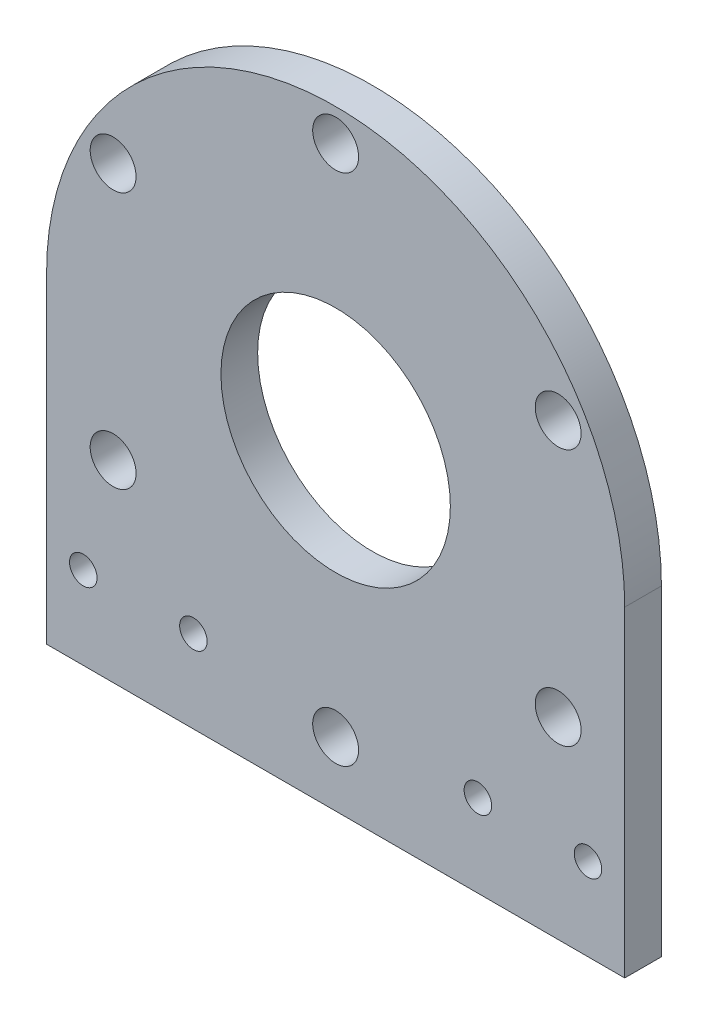
SolidWorks part; units mm, degrees
material "Thornel Mat VMA"
ref_plane "前视基准面" through (0, 0, 0) normal (0, 0, 1) x (1, 0, 0)
ref_plane "上视基准面" through (0, 0, 0) normal (0, 1, 0) x (1, 0, 0)
ref_plane "右视基准面" through (0, 0, 0) normal (1, 0, 0) x (0, 0, -1)
sketch "草图1" plane through (0, 0, 0) normal (0, 0, 1) x (1, 0, 0)
  line L0 (-31.5, 0) -> (-31.5, -35)
  line L1 (-31.5, -35) -> (31.5, -35)
  line L2 (31.5, -35) -> (31.5, 0)
  circle A0 centre (0, 0) radius 31.5
  dimension "D1" = 63
  dimension "D2" = 35
extrude "凸台-拉伸1" add sketch "草图1" along normal blind 4 contours A0 | A0 L0 L1 L2
sketch "草图2" plane through (0, 0, 4) normal (0, 0, 1) x (1, 0, 0)
  circle A0 centre (0, 0) radius 12.5
  circle A1 centre (0, 0) radius 28 construction
  circle A2 centre (0, 28) radius 2.5
  circle A3 centre (24.2487, -14) radius 2.5
  circle A4 centre (-24.2487, -14) radius 2.5
  circle A5 centre (0, -28) radius 2.5
  circle A6 centre (-24.2487, 14) radius 2.5
  circle A7 centre (24.2487, 14) radius 2.5
  point P8 (0, 0)
  point P13 (0, 0)
  point P14 (0, 28)
  point P15 (0, 0)
  point P20 (0, 0)
  dimension "D1" = 25
  dimension "D2" = 56
  dimension "D3" = 5
  dimension "D4" = 3
extrude "切除-拉伸1" cut sketch "草图2" against normal through all
sketch "草图3" plane through (0, 0, 4) normal (0, 0, 1) x (1, 0, 0)
  line L0 (-31.5, -26) -> (31.5, -26) construction
  line L1 (-31.5, 0) -> (-31.5, -35) construction
  line L2 (31.5, -35) -> (31.5, 0) construction
  line L3 (-31.5, -35) -> (31.5, -35) construction
  line L4 (0, -35) -> (0, -26) construction
  circle A0 centre (-27.5, -26) radius 1.5
  circle A3 centre (-15.5, -26) radius 1.5
  circle A4 centre (15.5, -26) radius 1.5
  circle A5 centre (27.5, -26) radius 1.5
  dimension "D1" = 9
  dimension "D2" = 3
  dimension "D3" = 12
  dimension "D4" = 4
extrude "切除-拉伸2" cut sketch "草图3" against normal through all
